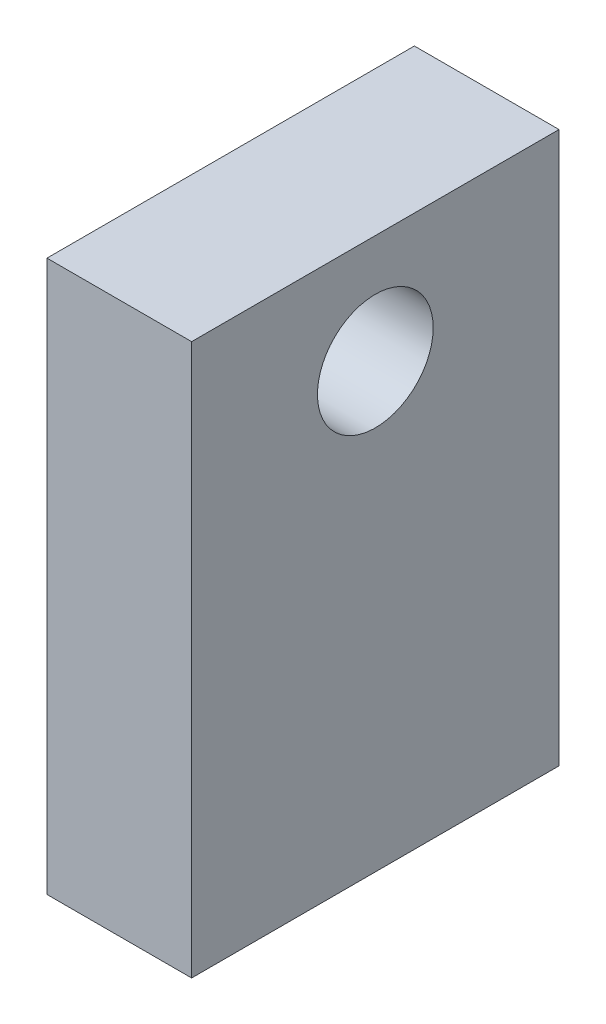
SolidWorks part; units mm, degrees
ref_plane "Front" through (0, 0, 0) normal (0, 0, 1) x (1, 0, 0)
ref_plane "Top" through (0, 0, 0) normal (0, 1, 0) x (1, 0, 0)
ref_plane "Right" through (0, 0, 0) normal (1, 0, 0) x (0, 0, -1)
sketch "Sketch1" plane through (0, 0, 0) normal (1, 0, 0) x (0, 0, -1)
  line L0 (6.35, 19.05) -> (6.35, 0)
  line L1 (0, 0) -> (12.7, 0)
  line L2 (0, 0) -> (0, 19.05)
  line L3 (0, 19.05) -> (12.7, 19.05)
  line L4 (12.7, 0) -> (12.7, 19.05)
  circle A0 centre (6.35, 15.2929) radius 2
  dimension "D1" = 12.7
  dimension "D2" = 19.05
extrude "Boss-Extrude1" add sketch "Sketch1" along normal blind 5 contours A0 L0 L3 L2 L1 | A0 L0 L1 L4 L3
